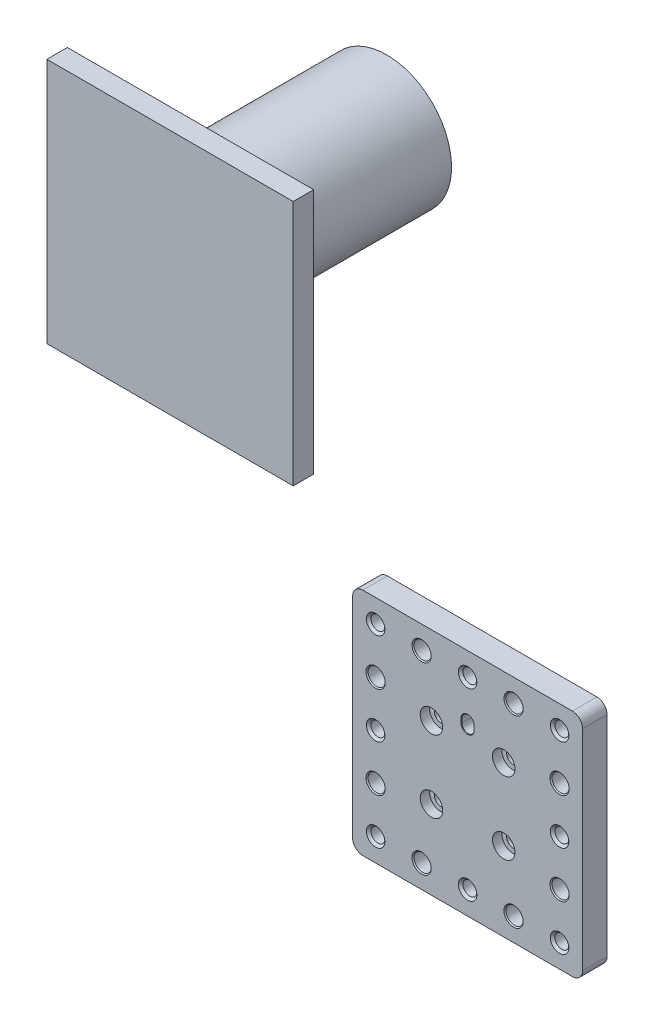
SolidWorks part; units mm, degrees
ref_plane "Front Plane" through (0, 0, 0) normal (0, 0, 1) x (1, 0, 0)
ref_plane "Top Plane" through (0, 0, 0) normal (0, 1, 0) x (1, 0, 0)
ref_plane "Right Plane" through (0, 0, 0) normal (1, 0, 0) x (0, 0, -1)
ref_plane "Plane1" through (0, 0, 12) normal (0, 0, 1) x (1, 0, 0)
sketch "Sketch1" plane through (0, 0, 12) normal (0, 0, 1) x (1, 0, 0)
  line L0 (-56.25, -56.25) -> (56.25, -56.25)
  line L1 (56.25, -56.25) -> (56.25, 56.25)
  line L2 (56.25, 56.25) -> (-56.25, 56.25)
  line L3 (-56.25, 56.25) -> (-56.25, -56.25)
extrude "Boss-Extrude1" add sketch "Sketch1" against normal blind 12
fillet "Fillet1" radius 5 4 edges at (-56.25, 56.25, 6) (56.25, 56.25, 6) (-56.25, -56.25, 6) (56.25, -56.25, 6)
sketch "Sketch3" plane through (0, 0, 0) normal (0, 1, 0) x (1, 0, 0)
  line L0 (0, 0) -> (-31.7, 0)
  line L1 (-31.7, 0) -> (-31.7, -4)
  line L2 (-31.7, -4) -> (0, -4)
  line L3 (0, -4) -> (0, 0)
  line L4 (0, -4) -> (0, 0) construction
  dimension "D1" = 31.7
revolve "Cut-Revolve1" cut sketch "Sketch3" angle 360 about L4
chamfer "Chamfer4" [suppressed] distance 0.5 angle 45
sketch "Sketch2" plane through (0, 0, 0) normal (0, 0, -1) x (-1, 0, 0)
  line L0 (3, 24) -> (3, 26) construction
  line L1 (-3, 26) -> (-3, 24) construction
  line L2 (0, 26) -> (0, 24) construction
  line L3 (3, 26) -> (3, 24)
  line L4 (-3, 26) -> (-3, 24)
  arc A0 (3, 26) -> (-3, 26) centre (0, 26) ccw construction
  arc A1 (-3, 24) -> (3, 24) centre (0, 24) ccw construction
  arc A2 (3, 26) -> (-3, 26) centre (0, 26) ccw
  arc A3 (-3, 24) -> (3, 24) centre (0, 24) ccw
  point P6 (0, 25)
  dimension "D1" = 3
extrude "Cut-Extrude1" cut sketch "Sketch2" against normal through all
chamfer "Chamfer3" distance 0.25 angle 45 8 edges at (0, 29, 4) (-3, 25, 4) (3, 25, 4) (0, 21, 4) (0, 29, 12) (-3, 25, 12) (3, 25, 12) (0, 21, 12)
hole_wizard "CBORE for M6 Hex Head Bolt1" positions "Sketch11" profile "Sketch10" counterbore size "M6" standard "ANSI Metric" end condition through all
sketch "Sketch11" plane through (0, 0, 12) normal (0, 0, 1) x (1, 0, 0)
  point P0 (-17.6777, -17.6777)
  point P1 (17.6777, -17.6777)
  point P2 (17.6777, 17.6777)
  point P3 (-17.6777, 17.6777)
sketch "Sketch10" plane through (-17.6777, -17.6777, 12) normal (1, 0, 0) x (0, -1, 0)
  line L0 (0, 0) -> (0, 12)
  line L1 (0, 12) -> (3.2, 12)
  line L3 (3.2, 12) -> (3.2, 4.6)
  line L4 (3.2, 4.6) -> (5.5, 4.6)
  line L5 (5.5, 4.6) -> (5.5, 0)
  line L7 (5.5, 0) -> (0, 0)
  line L11 (0, -6.35) -> (0, 107.95) construction
  dimension "Thru Hole Dia." = 6.4
  dimension "Thru Hole Depth" = 12
  dimension "C'Bore Dia." = 11
  dimension "C'Bore Depth" = 4.6
hole_wizard "Ø6.8 (6.8) Diameter Hole1" positions "Sketch5" profile "Sketch4" hole size "Ø6.8" standard "ANSI Metric"
sketch "Sketch5" plane through (0, 0, 12) normal (0, 0, 1) x (1, 0, 0)
  point P0 (-45, 0)
  point P1 (-45, 45)
  point P2 (0, -45)
  point P3 (45, -45)
  point P4 (-45, -45)
sketch "Sketch4" plane through (-45, 0, 12) normal (1, 0, 0) x (0, -1, 0)
  line L0 (0, 0) -> (0, 12)
  line L1 (0, 12) -> (3.4, 12)
  line L2 (3.4, 12) -> (3.4, 0)
  line L5 (3.4, 0) -> (0, 0)
  line L11 (0, -6.35) -> (0, 107.95) construction
  dimension "Thru Hole Dia." = 6.8
  dimension "Thru Hole Depth" = 12
hole_wizard "Ø6.8 (6.8) Diameter Hole2" positions "Sketch7" profile "Sketch6" hole size "Ø6.8" standard "ANSI Metric"
sketch "Sketch7" plane through (0, 0, 0) normal (0, 0, -1) x (-1, 0, 0)
  point P0 (-45, 0)
  point P1 (0, 45)
  point P2 (-45, 45)
sketch "Sketch6" plane through (45, 0, 0) normal (1, 0, 0) x (0, 1, 0)
  line L0 (0, 0) -> (0, 12)
  line L1 (0, 12) -> (3.4, 12)
  line L2 (3.4, 12) -> (3.4, 0)
  line L5 (3.4, 0) -> (0, 0)
  line L11 (0, -6.35) -> (0, 107.95) construction
  dimension "Thru Hole Dia." = 6.8
  dimension "Thru Hole Depth" = 12
chamfer "Chamfer1" distance 1.125 angle 45 16 edges at (3.4, -45, 0) (-41.6, 45, 0) (48.4, -45, 0) (-41.6, -45, 0) (41.6, 0, 12) (-41.6, 45, 12) (41.6, 0, 0) (3.4, -45, 12) (-3.4, 45, 12) (48.4, -45, 12) (-3.4, 45, 0) (41.6, 45, 12) (-41.6, -45, 12) (41.6, 45, 0) (-41.6, 0, 0) (-41.6, 0, 12)
hole_wizard "CBORE for M8 Hex Head Bolt1" positions "Sketch9" profile "Sketch8" counterbore size "M8" standard "ANSI Metric"
sketch "Sketch9" plane through (0, 0, 0) normal (0, 0, -1) x (-1, 0, 0)
  point P0 (-45, 22.5)
  point P1 (-22.5, 45)
  point P2 (45, 22.5)
  point P3 (22.5, 45)
  point P4 (45, -22.5)
  point P5 (22.5, -45)
  point P6 (-45, -22.5)
  point P7 (-22.5, -45)
sketch "Sketch8" plane through (45, 22.5, 0) normal (1, 0, 0) x (0, 1, 0)
  line L0 (0, 0) -> (0, 12)
  line L1 (0, 12) -> (4.2, 12)
  line L3 (4.2, 12) -> (4.2, 5.6)
  line L4 (4.2, 5.6) -> (7.5, 5.6)
  line L5 (7.5, 5.6) -> (7.5, 0)
  line L7 (7.5, 0) -> (0, 0)
  line L11 (0, -6.35) -> (0, 107.95) construction
  dimension "Thru Hole Dia." = 8.4
  dimension "Thru Hole Depth" = 12
  dimension "C'Bore Dia." = 15
  dimension "C'Bore Depth" = 5.6
chamfer "Chamfer2" distance 0.5 angle 45 8 edges at (-26.7, -45, 12) (18.3, -45, 12) (40.8, 22.5, 12) (18.3, 45, 12) (-49.2, -22.5, 12) (40.8, -22.5, 12) (-49.2, 22.5, 12) (-26.7, 45, 12)
sketch "Sketch12" [suppressed] plane through (0, 0, 0) normal (0, 0, -1) x (-1, 0, 0)
  line L4 (56.25, -56.25) -> (56.25, 56.25)
  line L5 (56.25, 56.25) -> (-56.25, 56.25)
  line L6 (-56.25, 56.25) -> (-56.25, -56.25)
  line L7 (-56.25, -56.25) -> (56.25, -56.25)
  line L8 (56.25, -56.25) -> (56.25, 56.25)
  line L9 (56.25, 56.25) -> (-56.25, 56.25)
  line L10 (-56.25, 56.25) -> (-56.25, -56.25)
  line L11 (-56.25, -56.25) -> (56.25, -56.25)
  circle A2 centre (0, 0) radius 41.5
  circle A3 centre (0, 0) radius 41.5
  dimension "D1" = 10
  dimension "D2" = 0
extrude "Cut-Extrude2" [suppressed] cut sketch "Sketch12" against normal through all both and the other way through all
sketch "Sketch13" plane through (0, 0, 4) normal (0, 0, -1) x (-1, 0, 0)
  line L2 (213.8094, 75.3676) -> (93.3094, 75.3676)
  line L3 (213.8094, 75.3676) -> (213.8094, 195.8676)
  line L4 (213.8094, 195.8676) -> (93.3094, 195.8676)
  line L5 (93.3094, 75.3676) -> (93.3094, 195.8676)
  line L6 (213.8094, 75.3676) -> (93.3094, 195.8676) construction
  line L7 (213.8094, 195.8676) -> (93.3094, 75.3676) construction
  circle A0 centre (136.3778, -19.7745) radius 31.7
  point P5 (153.5594, 135.6176)
  dimension "D1" = 63.4
  dimension "D2" = 120.5
  dimension "D3" = 120.5
extrude "Boss-Extrude5" add sketch "Sketch13" along normal blind 10 separate body contours L4 L5 L2 L3
sketch "Sketch20" plane through (0, 0, -6) normal (0, 0, -1) x (-1, 0, 0)
  line L0 (56.25, 51.25) -> (56.25, -51.25) construction
  line L1 (213.8094, 75.3676) -> (213.8094, 195.8676) construction
  line L2 (93.3094, 75.3676) -> (93.3094, 195.8676) construction
  circle A0 centre (157.5594, 139.1758) radius 31.7
  point P11 (11.1569, 179.2562)
  dimension "D1" = 63.4
  dimension "D2" = 56.25
  dimension "D3" = 56.25
  dimension "D4" = 64.25
extrude "Boss-Extrude6" add sketch "Sketch20" along normal blind 100 contours A0
